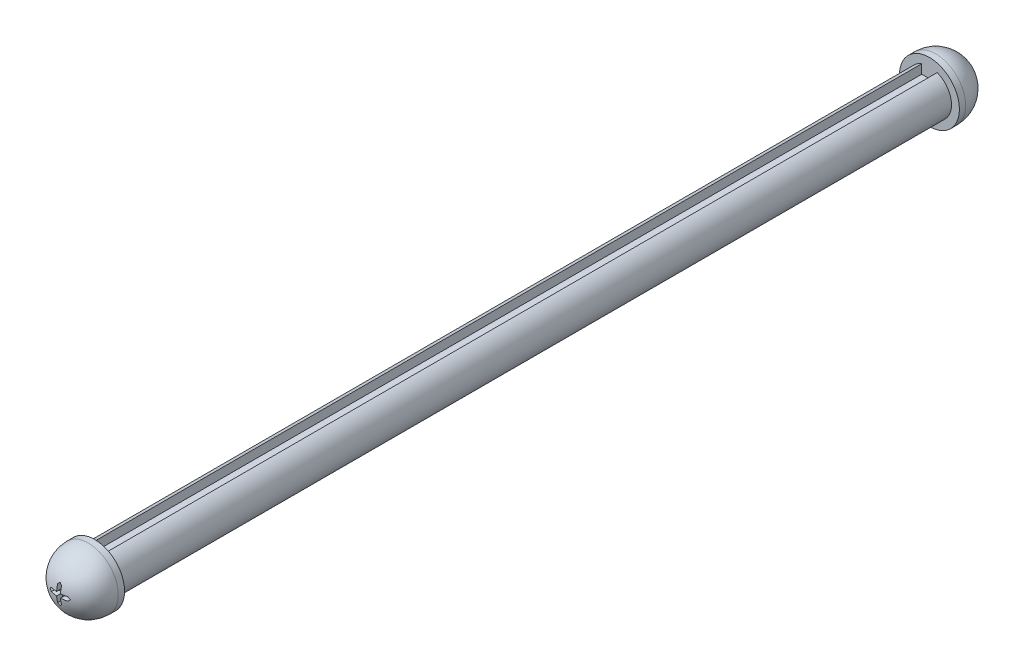
SolidWorks part; units mm, degrees
material "AISI 1020"
ref_plane "Front Plane" through (0, 0, 0) normal (0, 0, 1) x (1, 0, 0)
ref_plane "Top Plane" through (0, 0, 0) normal (0, 1, 0) x (1, 0, 0)
ref_plane "Right Plane" through (0, 0, 0) normal (1, 0, 0) x (0, 0, -1)
sketch "Sketch2" plane through (0, 0, 0) normal (0, 0, 1) x (1, 0, 0)
  line L0 (-1.225, 1.8286) -> (1.225, 1.8286)
  line L2 (-1.225, 1.8286) -> (-1.225, 3.2786)
  line L3 (1.225, 1.8286) -> (1.225, 3.2786)
  arc A0 (-1.225, 3.2786) -> (1.225, 3.2786) centre (0, 0) ccw
  point P6 (0, 1.8286)
  dimension "D1" = 7
  dimension "D2" = 2.45
  dimension "D3" = 1.45
extrude "Boss-Extrude1" add sketch "Sketch2" along normal blind 132.4
sketch "Sketch3" plane through (0, 0, 0) normal (0, 0, -1) x (-1, 0, 0)
  circle A0 centre (0, 0) radius 4.75
  dimension "D1" = 9.5
extrude "Boss-Extrude2" add sketch "Sketch3" along normal blind 1
sketch "Sketch4" plane through (0, 0, 0) normal (0, 1, 0) x (1, 0, 0)
  line L0 (4.75, 1) -> (-4.75, 1) construction
  line L1 (0, 1) -> (4.75, 1)
  line L2 (0, 5.75) -> (0, 1)
  arc A0 (4.75, 1) -> (0, 5.75) centre (0, 1) ccw
revolve "Revolve1" add sketch "Sketch4" angle 360 about L2
ref_plane "Plane1" through (0, 0, -5.75) normal (0, 0, -1) x (-1, 0, 0)
sketch "Sketch5" plane through (0, 0, -5.75) normal (0, 0, -1) x (-1, 0, 0)
  line L0 (0, 1.6) -> (-0.3, 1.3)
  line L1 (0, 55) -> (0, -55) construction
  line L2 (-0.3, 1.3) -> (-0.3, 0.3)
  line L3 (-0.3, 0.3) -> (-1.3, 0.3)
  line L4 (-1.3, 0.3) -> (-1.6, 0)
  line L5 (55, 0) -> (-55, 0) construction
  line L6 (0, 2.1683) -> (0, -1.7247) construction
  line L7 (-2.0371, 0) -> (5.0744, 0) construction
  line L8 (2.1683, 0) -> (-1.7247, 0) construction
  line L9 (1.3, 0.3) -> (0.3, 0.3)
  line L10 (1.6, 0) -> (1.3, 0.3)
  line L11 (0.3, 1.3) -> (0, 1.6)
  line L12 (0.3, 0.3) -> (0.3, 1.3)
  line L13 (0, -2.1683) -> (0, 1.7247) construction
  line L14 (0.3, -1.3) -> (0.3, -0.3)
  line L15 (0, -1.6) -> (0.3, -1.3)
  line L16 (1.3, -0.3) -> (1.6, 0)
  line L17 (0.3, -0.3) -> (1.3, -0.3)
  line L18 (-2.1683, 0) -> (1.7247, 0) construction
  line L19 (-1.3, -0.3) -> (-0.3, -0.3)
  line L20 (-1.6, 0) -> (-1.3, -0.3)
  line L21 (-0.3, -1.3) -> (0, -1.6)
  line L22 (-0.3, -0.3) -> (-0.3, -1.3)
  point P38 (0, 0)
  dimension "D1" = 0.3
  dimension "D2" = 0.3
  dimension "D3" = 1.6
  dimension "D4" = 4
extrude "Cut-Extrude1" cut sketch "Sketch5" against normal blind 1 draft 1 draft outward yes
ref_plane "Plane2" through (0, 0, 66.2) normal (0, 0, 1) x (1, 0, 0)
mirror "Mirror1" about plane through (0, 0, 66.2) normal (0, 0, 1) of "Cut-Extrude1", "Revolve1", "Boss-Extrude2"
equation "\"shaft_d\"= 7mm"
equation "\"D1@Sketch2\"=\"shaft_d\""
equation "\"shaft_l\"= 100mm"
equation "\"D1@Boss-Extrude1\"=\"shaft_l\" + 32.4"
